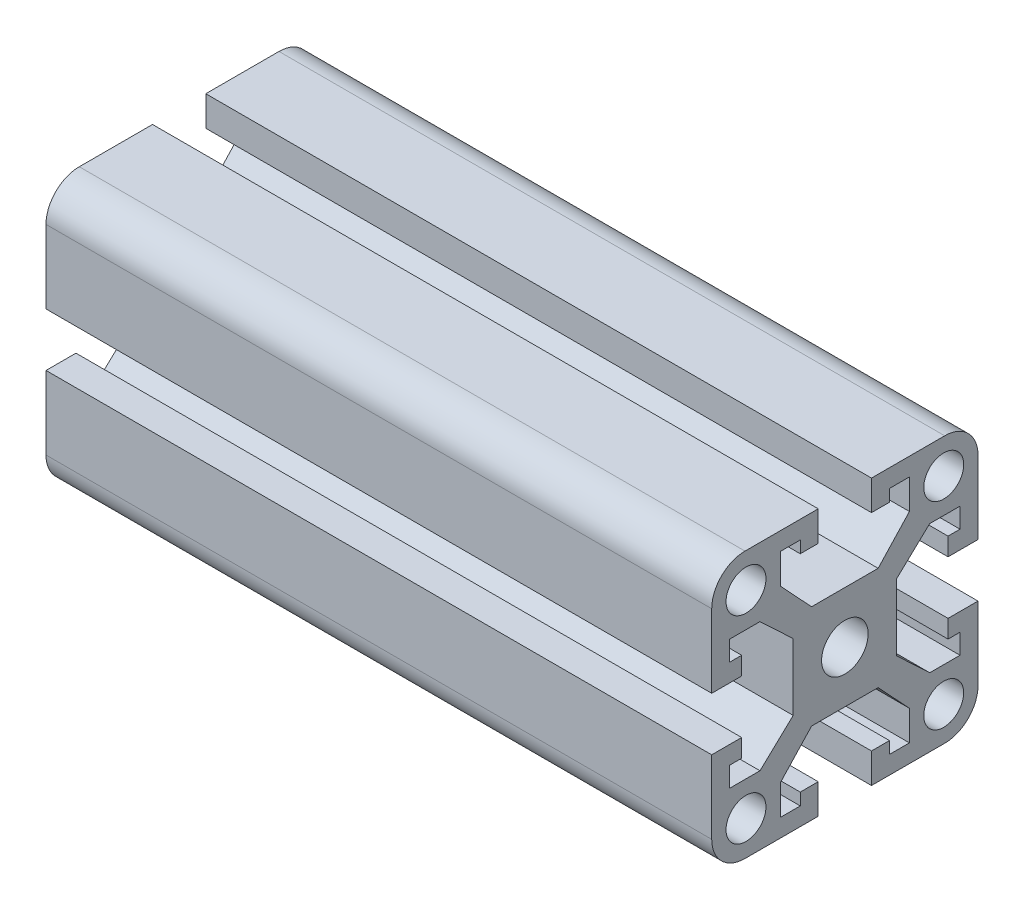
SolidWorks part; units mm, degrees
ref_plane "前视基准面" through (0, 0, 0) normal (0, 0, 1) x (1, 0, 0)
ref_plane "上视基准面" through (0, 0, 0) normal (0, 1, 0) x (1, 0, 0)
ref_plane "右视基准面" through (0, 0, 0) normal (1, 0, 0) x (0, 0, -1)
other "Configuration Table"
sketch "草图1" plane through (0, 0, 0) normal (1, 0, 0) x (0, 0, -1)
  line L1 (20.705, 55.0358) -> (60.705, 55.0358)
  line L2 (20.705, 55.0358) -> (20.705, 15.0358)
  line L3 (20.705, 15.0358) -> (60.705, 15.0358)
  line L4 (60.705, 55.0358) -> (60.705, 15.0358)
  dimension "D1" = 40
  dimension "D2" = 40
extrude "凸台-拉伸1" add sketch "草图1" along normal blind 100
sketch "草图2" plane through (100, 0, 0) normal (1, 0, 0) x (0, 0, -1)
  line L0 (40.705, 55.0358) -> (40.705, 15.0358) construction
  line L1 (60.705, 55.0358) -> (20.705, 55.0358) construction
  line L2 (20.705, 15.0358) -> (60.705, 15.0358) construction
  line L3 (20.705, 35.0358) -> (60.705, 35.0358) construction
  line L4 (20.705, 55.0358) -> (20.705, 15.0358) construction
  line L5 (60.705, 15.0358) -> (60.705, 55.0358) construction
  line L6 (36.705, 15.0358) -> (36.705, 19.5358)
  line L7 (36.705, 15.0358) -> (44.705, 15.0358)
  line L8 (36.705, 19.5358) -> (34.005, 19.5358)
  line L9 (34.005, 19.5358) -> (34.005, 17.7358)
  line L10 (34.005, 17.7358) -> (31.005, 17.7358)
  line L11 (31.005, 17.7358) -> (31.005, 22.2358)
  line L12 (45.705, 27.2758) -> (35.705, 27.2758)
  line L13 (31.005, 22.2358) -> (35.705, 27.2758)
  line L14 (50.405, 22.2358) -> (45.705, 27.2758)
  line L15 (50.405, 17.7358) -> (50.405, 22.2358)
  line L16 (47.405, 17.7358) -> (50.405, 17.7358)
  line L17 (47.405, 19.5358) -> (47.405, 17.7358)
  line L18 (44.705, 19.5358) -> (47.405, 19.5358)
  line L19 (44.705, 15.0358) -> (44.705, 19.5358)
  line L20 (44.705, 55.0358) -> (44.705, 50.5358)
  line L21 (44.705, 50.5358) -> (47.405, 50.5358)
  line L22 (47.405, 50.5358) -> (47.405, 52.3358)
  line L23 (47.405, 52.3358) -> (50.405, 52.3358)
  line L24 (50.405, 52.3358) -> (50.405, 47.8358)
  line L25 (50.405, 47.8358) -> (45.705, 42.7958)
  line L26 (31.005, 47.8358) -> (35.705, 42.7958)
  line L27 (45.705, 42.7958) -> (35.705, 42.7958)
  line L28 (31.005, 52.3358) -> (31.005, 47.8358)
  line L29 (34.005, 52.3358) -> (31.005, 52.3358)
  line L30 (34.005, 50.5358) -> (34.005, 52.3358)
  line L31 (36.705, 50.5358) -> (34.005, 50.5358)
  line L32 (36.705, 55.0358) -> (44.705, 55.0358)
  line L33 (36.705, 55.0358) -> (36.705, 50.5358)
  line L62 (20.705, 31.0358) -> (20.705, 39.0358)
  line L63 (20.705, 39.0358) -> (25.205, 39.0358)
  line L64 (25.205, 39.0358) -> (25.205, 41.7358)
  line L65 (25.205, 41.7358) -> (23.405, 41.7358)
  line L66 (23.405, 41.7358) -> (23.405, 44.7358)
  line L67 (23.405, 44.7358) -> (27.955, 44.7358)
  line L68 (32.945, 30.0358) -> (32.945, 40.0358)
  line L69 (32.945, 40.0358) -> (27.955, 44.7358)
  line L70 (32.945, 30.0358) -> (27.955, 25.3358)
  line L71 (23.405, 25.3358) -> (27.955, 25.3358)
  line L72 (23.405, 28.3358) -> (23.405, 25.3358)
  line L73 (25.205, 28.3358) -> (23.405, 28.3358)
  line L74 (25.205, 31.0358) -> (25.205, 28.3358)
  line L75 (20.705, 31.0358) -> (25.205, 31.0358)
  line L76 (60.705, 31.0358) -> (56.205, 31.0358)
  line L77 (56.205, 31.0358) -> (56.205, 28.3358)
  line L78 (56.205, 28.3358) -> (58.005, 28.3358)
  line L79 (58.005, 28.3358) -> (58.005, 25.3358)
  line L80 (58.005, 25.3358) -> (53.455, 25.3358)
  line L81 (48.465, 30.0358) -> (53.455, 25.3358)
  line L82 (48.465, 40.0358) -> (53.455, 44.7358)
  line L83 (48.465, 30.0358) -> (48.465, 40.0358)
  line L84 (58.005, 44.7358) -> (53.455, 44.7358)
  line L85 (58.005, 41.7358) -> (58.005, 44.7358)
  line L86 (56.205, 41.7358) -> (58.005, 41.7358)
  line L87 (56.205, 39.0358) -> (56.205, 41.7358)
  line L88 (60.705, 39.0358) -> (56.205, 39.0358)
  line L89 (60.705, 31.0358) -> (60.705, 39.0358)
  line L90 (31.005, 47.8358) -> (31.005, 44.7358) construction
  line L91 (31.005, 44.7358) -> (27.955, 44.7358) construction
  line L92 (31.005, 52.3358) -> (31.005, 55.0358) construction
  circle A0 centre (40.705, 35.0358) radius 3.5
  circle A1 centre (25.855, 49.8858) radius 3
  circle A2 centre (25.855, 20.1858) radius 3
  circle A3 centre (55.555, 49.8858) radius 3
  circle A4 centre (55.555, 20.1858) radius 3
  point P22 (40.705, 27.2758)
  point P41 (40.705, 42.7958)
  point P52 (32.945, 35.0358)
  point P71 (48.465, 35.0358)
  dimension "D17" = 7
  dimension "D20" = 6
  dimension "D1" = 4
  dimension "D2" = 2.7
  dimension "D3" = 4.5
  dimension "D4" = 2.7
  dimension "D5" = 3
  dimension "D6" = 4.5
  dimension "D7" = 12.24
  dimension "D8" = 5
  dimension "D9" = 4
  dimension "D10" = 2.7
  dimension "D11" = 3
  dimension "D12" = 4.5
  dimension "D13" = 2.7
  dimension "D14" = 4.55
  dimension "D15" = 12.24
  dimension "D16" = 5
  dimension "D18" = 5.15
  dimension "D19" = 5.15
extrude "切除-拉伸1" cut sketch "草图2" against normal up to next
fillet "圆角1" radius 5 4 edges at (50, 15.0358, -20.705) (50, 15.0358, -60.705) (50, 55.0358, -60.705) (50, 55.0358, -20.705)
sketch "草图3" plane through (0, 42.7958, 0) normal (0, 1, 0) x (1, 0, 0)
  line L0 (0, 40.705) -> (71.1062, 40.705) construction
  line L1 (0, 45.705) -> (0, 35.705) construction
  line L2 (0, 55.705) -> (0, 44.705) construction
  circle A0 centre (50, 40.705) radius 1.2367
  dimension "D1" = 50
extrude "切除-拉伸2" cut sketch "草图3" against normal blind 0.5
